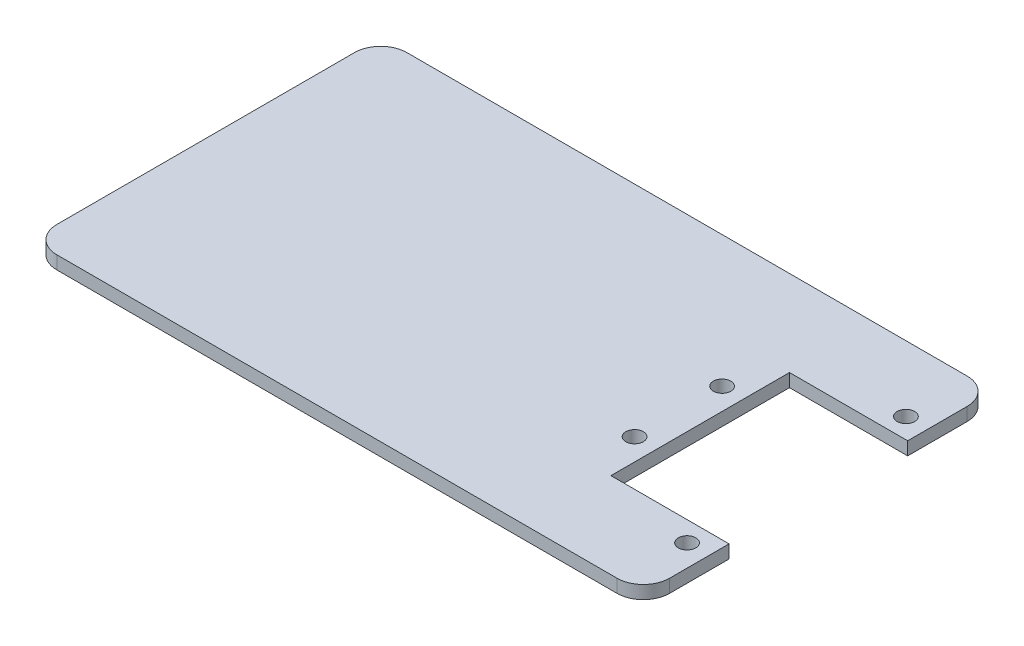
SolidWorks part; units mm, degrees
ref_plane "Спереди" through (0, 0, 0) normal (0, 0, 1) x (1, 0, 0)
ref_plane "Сверху" through (0, 0, 0) normal (0, 1, 0) x (1, 0, 0)
ref_plane "Справа" through (0, 0, 0) normal (1, 0, 0) x (0, 0, -1)
sketch "Эскиз1" plane through (0, 0, 0) normal (0, 1, 0) x (1, 0, 0)
  line L1 (35, -20) -> (-35, -20)
  line L2 (35, -20) -> (35, 20)
  line L3 (35, 20) -> (-35, 20)
  line L4 (-35, -20) -> (-35, 20)
  line L5 (35, -20) -> (-35, 20) construction
  line L6 (35, 20) -> (-35, -20) construction
  point P0 (0, 0)
  dimension "D1" = 70
  dimension "D2" = 40
extrude "Бобышка-Вытянуть1" add sketch "Эскиз1" along normal blind 1.5
fillet "Скругление1" radius 3 4 edges at (-35, 0.75, -20) (35, 0.75, -20) (35, 0.75, 20) (-35, 0.75, 20)
sketch "Эскиз2" plane through (0, 1.5, 0) normal (0, 1, 0) x (1, 0, 0)
  line L0 (35, -17) -> (35, 17) construction
  line L1 (35, 10.2) -> (21.5, 10.2)
  line L2 (35, 10.2) -> (35, -10.2)
  line L3 (35, -10.2) -> (21.5, -10.2)
  line L4 (21.5, 10.2) -> (21.5, -10.2)
  line L5 (32, 20) -> (-32, 20) construction
  line L6 (-32, -20) -> (32, -20) construction
  dimension "D1" = 13.5
  dimension "D2" = 9.8
  dimension "D3" = 9.8
extrude "Вырез-Вытянуть1" cut sketch "Эскиз2" against normal through all
sketch "Эскиз3" plane through (0, 0, 0) normal (0, -1, 0) x (1, 0, 0)
  line L0 (35, -10.2) -> (35, -17) construction
  line L2 (0, 0) -> (21.5, 0) construction
  line L3 (21.5, -10.2) -> (21.5, 10.2) construction
  line L6 (32, -20) -> (-32, -20) construction
  circle A0 centre (19, -5) radius 1
  circle A1 centre (19, 5) radius 1
  circle A2 centre (32.5, -12.5) radius 1
  circle A3 centre (32.5, 12.5) radius 1
  dimension "D1" = 16
  dimension "D2" = 2
  dimension "D4" = 2
  dimension "D3" = 15
  dimension "D5" = 7.5
  dimension "D6" = 2.5
extrude "Вырез-Вытянуть2" cut sketch "Эскиз3" against normal through all
